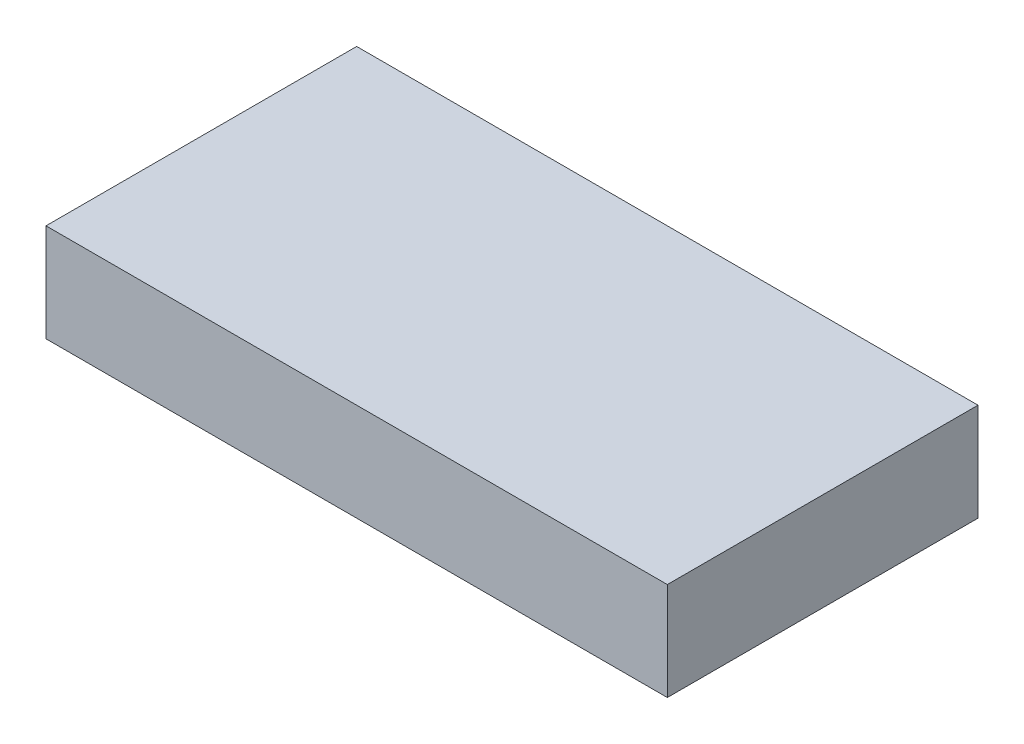
SolidWorks part; units mm, degrees
ref_plane "Front Plane" through (0, 0, 0) normal (0, 0, 1) x (1, 0, 0)
ref_plane "Top Plane" through (0, 0, 0) normal (0, 1, 0) x (1, 0, 0)
ref_plane "Right Plane" through (0, 0, 0) normal (1, 0, 0) x (0, 0, -1)
sketch "Sketch1" plane through (0, 0, 0) normal (0, 1, 0) x (1, 0, 0)
  line L1 (0, 0) -> (40, 0)
  line L2 (0, 0) -> (0, 20)
  line L3 (0, 20) -> (40, 20)
  line L4 (40, 0) -> (40, 20)
extrude "Boss-Extrude1" add sketch "Sketch1" against normal blind 6.3
